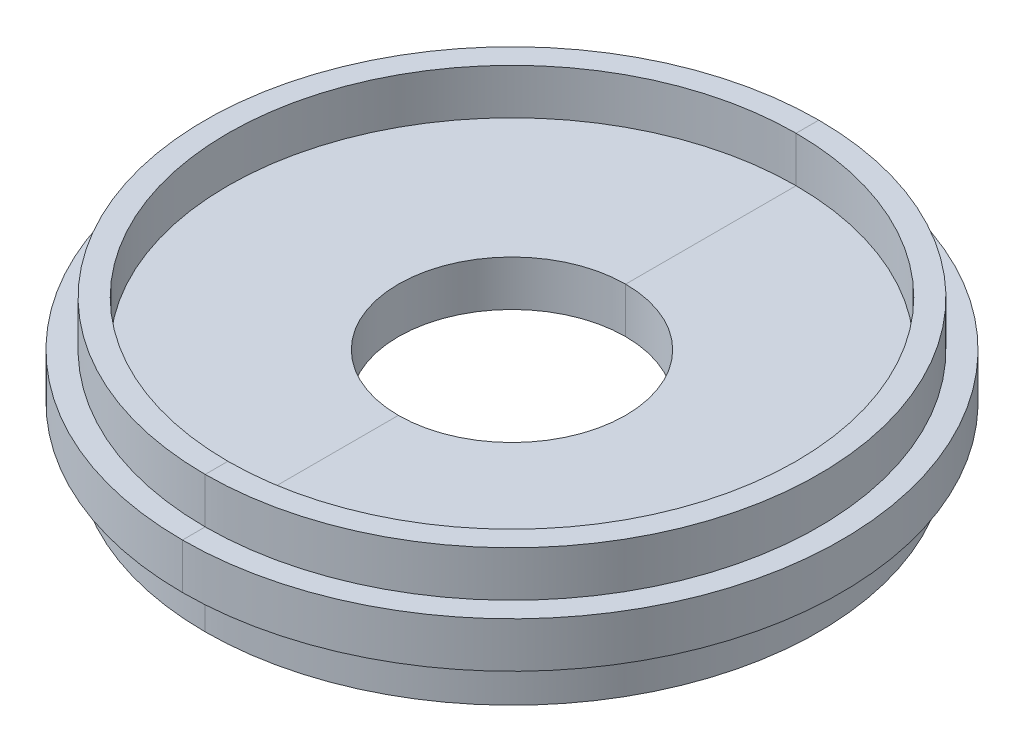
SolidWorks part; units mm, degrees
ref_plane "Front Plane" through (0, 0, 0) normal (0, 0, 1) x (1, 0, 0)
ref_plane "Top Plane" through (0, 0, 0) normal (0, 1, 0) x (1, 0, 0)
ref_plane "Right Plane" through (0, 0, 0) normal (1, 0, 0) x (0, 0, -1)
sketch "Sketch1" plane through (0, 0, 0) normal (0, 1, 0) x (1, 0, 0)
  circle A0 centre (0, 0) radius 92.075
  circle A1 centre (0, 0) radius 31.75
  dimension "D1" = 184.15
  dimension "D2" = 63.5
extrude "Boss-Extrude1" add sketch "Sketch1" along normal mid plane 12.7
sketch "Sketch5" plane through (0, 6.35, 0) normal (0, 1, 0) x (1, 0, 0)
  circle A0 centre (0, 0) radius 85.725
  circle A1 centre (0, 0) radius 79.375
  dimension "D1" = 171.45
  dimension "D2" = 158.75
extrude "Boss-Extrude2" add sketch "Sketch5" along normal blind 12.7
ref_plane "Plane1" through (0, 0, -85.725) normal (0, 0, -1) x (-1, 0, 0)
sketch "Sketch6" plane through (0, 0, -85.725) normal (0, 0, -1) x (-1, 0, 0)
  line L0 (0, 55) -> (0, -55) construction
  line L1 (92.075, 6.35) -> (-92.075, 6.35) construction
  circle A0 centre (0, 12.7) radius 1.4351
  dimension "D1" = 2.8702
  dimension "D2" = 6.35
extrude "Cut-Extrude1" [suppressed] cut sketch "Sketch6" against normal blind 12.7
pattern_circular "CirPattern1" [suppressed] count 12 over 360
mirror "Mirror1" about plane through (0, 0, 0) normal (0, 1, 0) of "CirPattern1", "Cut-Extrude1", "Boss-Extrude2"
sketch "Sketch7" plane through (0, 19.05, 0) normal (0, 1, 0) x (1, 0, 0)
  line L0 (-25.7878, 75.0692) -> (-28.1663, 80.9657)
  line L1 (28.1663, 80.9657) -> (25.7878, 75.0692)
  arc A0 (28.1663, 80.9657) -> (-28.1663, 80.9657) centre (0, 0) ccw
  circle A1 centre (0, 0) radius 85.725 construction
  arc A2 (25.7878, 75.0692) -> (-25.7878, 75.0692) centre (0, 0) ccw
  circle A3 centre (0, 0) radius 79.375 construction
extrude "Boss-Extrude3" add sketch "Sketch7" against normal up to surface (25.4 mm away)
mirror "Mirror3" about plane through (0, 0, 0) normal (0, 1, 0) of "Boss-Extrude3"
mirror "Mirror4" about plane through (0, 0, 0) normal (0, 0, 1) of "Boss-Extrude3"
mirror "Mirror5" about plane through (0, 0, 0) normal (0, 1, 0) of "Mirror4"
sketch "Sketch4" plane through (0, 0, 0) normal (0, 0, 1) x (1, 0, 0)
  line L0 (0, 23.2786) -> (0, -14.9525) construction
sketch "Sketch3" plane through (0, 0, 0) normal (0, 0, 1) x (1, 0, 0)
  line L0 (-31.75, -6.35) -> (-56.6752, 6.35)
  line L1 (92.075, 6.35) -> (-92.075, 6.35) construction
  line L2 (-56.6752, 6.35) -> (-31.75, 6.35)
  line L3 (-31.75, 6.35) -> (-31.75, -6.35)
  line L4 (-31.75, -6.35) -> (31.75, -6.35) construction
  line L5 (31.75, 6.35) -> (-31.75, 6.35) construction
  dimension "D1" = 27
revolve "Cut-Revolve1" [suppressed] cut sketch "Sketch3" angle 360 about L0
split "Split1" trim tools "Right Plane" bodies to split 114 resulting bodies 104 105
